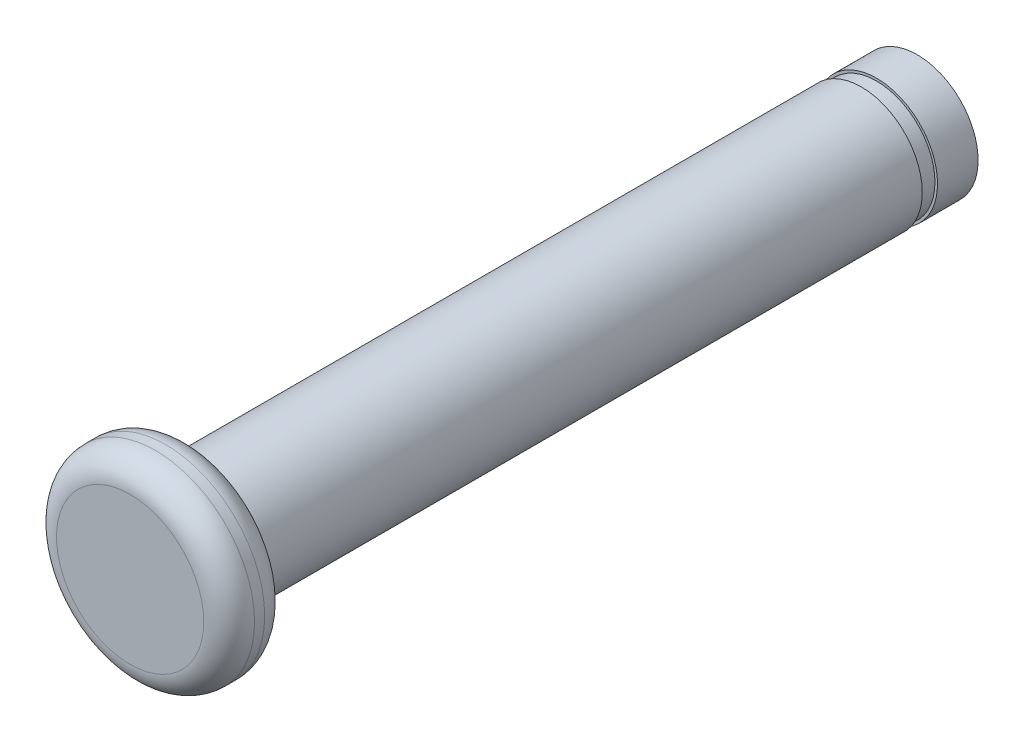
SolidWorks part; units mm, degrees
material "Gray Cast Iron (SN)"
ref_plane "Front Plane" through (0, 0, 0) normal (0, 0, 1) x (1, 0, 0)
ref_plane "Top Plane" through (0, 0, 0) normal (0, 1, 0) x (1, 0, 0)
ref_plane "Right Plane" through (0, 0, 0) normal (1, 0, 0) x (0, 0, -1)
sketch "Sketch1" plane through (0, 0, 0) normal (0, 0, 1) x (1, 0, 0)
  circle A0 centre (0, 0) radius 2.4765
  dimension "D1" = 4.953
extrude "Boss-Extrude1" add sketch "Sketch1" against normal blind 1.524
sketch "Sketch2" plane through (0, 0, -1.524) normal (0, 0, -1) x (-1, 0, 0)
  circle A0 centre (0, 0) radius 1.524
  dimension "D1" = 3.048
extrude "Boss-Extrude2" add sketch "Sketch2" along normal blind 18.161
sketch "Sketch4" plane through (0, 0, -19.685) normal (0, 0, -1) x (-1, 0, 0)
  circle A0 centre (0, 0) radius 1.524
extrude "Cut-Extrude1" cut sketch "Sketch4" against normal blind 1.397
sketch "Sketch5" plane through (0, 0, -18.288) normal (0, 0, -1) x (-1, 0, 0)
  circle A0 centre (0, 0) radius 1.4605
  dimension "D1" = 2.921
extrude "Boss-Extrude3" add sketch "Sketch5" along normal blind 0.381
sketch "Sketch6" plane through (0, 0, -18.669) normal (0, 0, -1) x (-1, 0, 0)
  circle A0 centre (0, 0) radius 1.524
  dimension "D1" = 3.048
extrude "Boss-Extrude4" add sketch "Sketch6" along normal blind 1.016
fillet "Fillet1" radius 0.635 2 edges at (2.4765, 0, 0) (2.4765, 0, -1.524)
